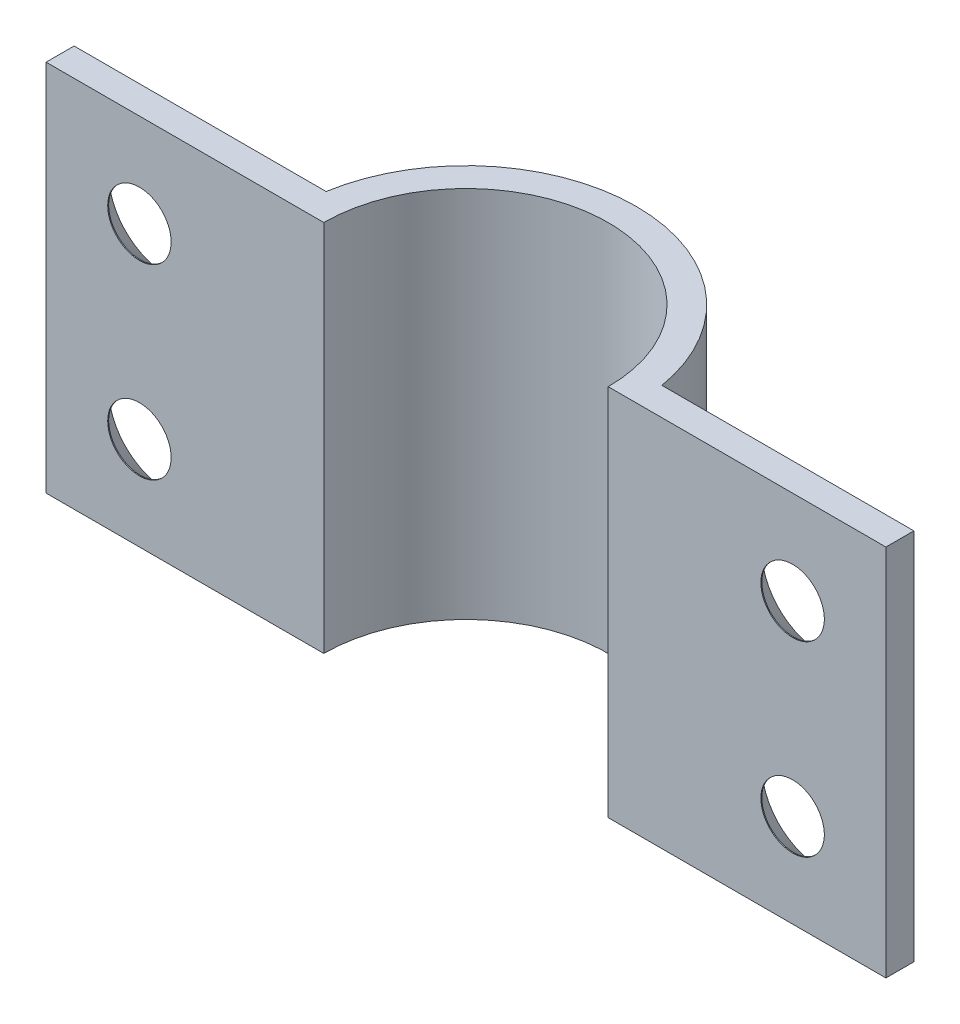
SolidWorks part; units mm, degrees
ref_plane "Front Plane" through (0, 0, 0) normal (0, 0, 1) x (1, 0, 0)
ref_plane "Top Plane" through (0, 0, 0) normal (0, 1, 0) x (1, 0, 0)
ref_plane "Right Plane" through (0, 0, 0) normal (1, 0, 0) x (0, 0, -1)
sketch "Sketch1" plane through (0, 0, 0) normal (0, 1, 0) x (1, 0, 0)
  line L0 (-7.62, 0) -> (-22.5, 0)
  line L1 (7.62, 0) -> (22.5, 0)
  line L2 (8.9958, 1.5) -> (22.5, 1.5)
  line L3 (-8.9958, 1.5) -> (-22.5, 1.5)
  line L4 (-22.5, 1.5) -> (-22.5, 0)
  line L5 (22.5, 1.5) -> (22.5, 0)
  arc A0 (7.62, 0) -> (-7.62, 0) centre (0, 0) ccw
  arc A1 (8.9958, 1.5) -> (-8.9958, 1.5) centre (0, 0) ccw
  dimension "D1" = 22.5
  dimension "D3" = 15.24
  dimension "D2" = 45
  dimension "D4" = 1.5
extrude "Boss-Extrude1" add sketch "Sketch1" along normal blind 20
sketch "Sketch2" plane through (0, 0, -1.5) normal (0, 0, -1) x (-1, 0, 0)
  line L0 (-22.5, 20) -> (-22.5, 0) construction
  line L1 (-22.5, 0) -> (-8.9958, 0) construction
  line L2 (8.9958, 0) -> (22.5, 0) construction
  line L3 (22.5, 20) -> (22.5, 0) construction
  line L4 (-22.5, 20) -> (-8.9958, 20) construction
  line L5 (8.9958, 20) -> (22.5, 20) construction
  point P0 (-17.5, 5)
  point P1 (17.5, 5)
  point P10 (-17.5, 15)
  point P11 (17.5, 15)
  dimension "D1" = 5
  dimension "D2" = 5
  dimension "D3" = 5
  dimension "D4" = 5
  dimension "D5" = 5
  dimension "D6" = 5
  dimension "D7" = 5
  dimension "D8" = 5
hole_wizard "CSK for M3 Countersunk Flat Head Screw1" positions "3DSketch1" profile "Sketch3" countersink size "M3" standard "ISO" end condition through all
sketch3d "3DSketch1"
  point P0 (17.5, 5, -1.5)
  point P3 (-17.5, 5, -1.5)
  point P6 (17.5, 15, -1.5)
  point P9 (-17.5, 15, -1.5)
sketch "Sketch3" plane through (17.5, 5, -1.5) normal (1, 0, 0) x (0, 1, 0)
  line L0 (0, 0) -> (0, 1.5)
  line L1 (0, 1.5) -> (1.7, 1.5)
  line L2 (1.7, 1.5) -> (1.7, 1.45)
  line L3 (1.7, 1.45) -> (3.15, 0)
  line L5 (3.15, 0) -> (0, 0)
  line L6 (-1.7, 1.45) -> (-3.15, 0) construction
  line L11 (0, -6.35) -> (0, 107.95) construction
  dimension "Thru Hole Dia." = 3.4
  dimension "Thru Hole Depth" = 1.5
  dimension "Near C'Sink Dia." = 6.3
  dimension "Near C'Sink Angle" = 90
